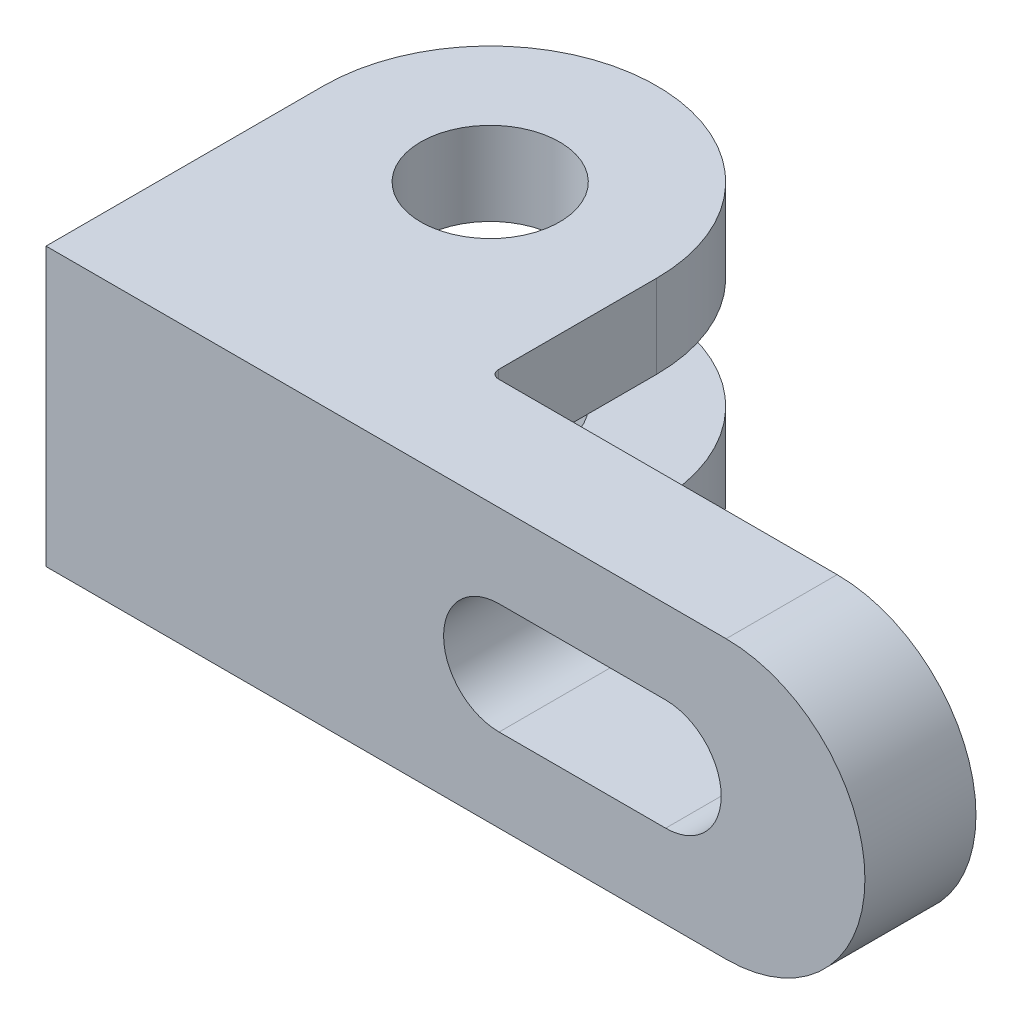
SolidWorks part; units mm, degrees
ref_plane "Front Plane" through (0, 0, 0) normal (0, 0, 1) x (1, 0, 0)
ref_plane "Top Plane" through (0, 0, 0) normal (0, 1, 0) x (1, 0, 0)
ref_plane "Right Plane" through (0, 0, 0) normal (1, 0, 0) x (0, 0, -1)
sketch "Sketch2" plane through (0, 0, 0) normal (0, 0, 1) x (1, 0, 0)
  line L1 (-59, 20) -> (59, 20)
  line L2 (-59, 20) -> (-59, -20)
  line L3 (-59, -20) -> (59, -20)
  line L4 (59, 20) -> (59, -20)
  line L5 (-59, 20) -> (59, -20) construction
  line L6 (-59, -20) -> (59, 20) construction
  circle A0 centre (39, 0) radius 20
  point P0 (0, 0)
  dimension "D1" = 118
  dimension "D2" = 40
extrude "Boss-Extrude1" add sketch "Sketch2" along normal mid plane 16 contours A0 L1 L2 L3 | A0
sketch "Sketch3" plane through (0, 0, 8) normal (0, 0, 1) x (1, 0, 0)
  line L1 (6.285, 8) -> (30.285, 8)
  line L2 (6.285, 8) -> (6.285, -8)
  line L3 (6.285, -8) -> (30.285, -8)
  line L4 (30.285, 8) -> (30.285, -8)
  line L5 (6.285, 8) -> (30.285, -8) construction
  line L6 (6.285, -8) -> (30.285, 8) construction
  circle A0 centre (30.285, 0) radius 8
  circle A1 centre (6.285, 0) radius 8
  point P0 (18.285, 0)
  dimension "D1" = 24
  dimension "D2" = 16
extrude "Cut-Extrude2" cut sketch "Sketch3" against normal through all contours L2 A1 | A1 L3 A0 L1 | L2 A1 | L4 A0 | L4 A0
sketch "Sketch5" plane through (0, 20, 0) normal (0, 1, 0) x (1, 0, 0)
  line L0 (-59, 8) -> (-11, 8)
  line L1 (-59, 8) -> (39, 8) construction
  line L2 (-11, 8) -> (-11, 32)
  line L3 (-59, 8) -> (-59, 32)
  line L4 (-59, 32) -> (-11, 32)
  circle A0 centre (-35, 32) radius 24
  line M3 (39, 8) -> (-59, 8)
extrude "Boss-Extrude2" add sketch "Sketch5" against normal blind 12 contours L4 A0 | L4 A0 | A0 L3 L0 | A0 L2 M3
sketch "Sketch6" plane through (0, 20, 0) normal (0, 1, 0) x (1, 0, 0)
  circle A0 centre (-35, 32) radius 10
extrude "Cut-Extrude3" cut sketch "Sketch6" against normal through all
mirror "Mirror1" about plane through (0, 0, 0) normal (0, 1, 0) of "Cut-Extrude3", "Boss-Extrude2"
fillet "Fillet2" radius 1.2 1 edges at (-11, 14, -8)
fillet "Fillet3" radius 1.2 1 edges at (-11, -14, -8)
